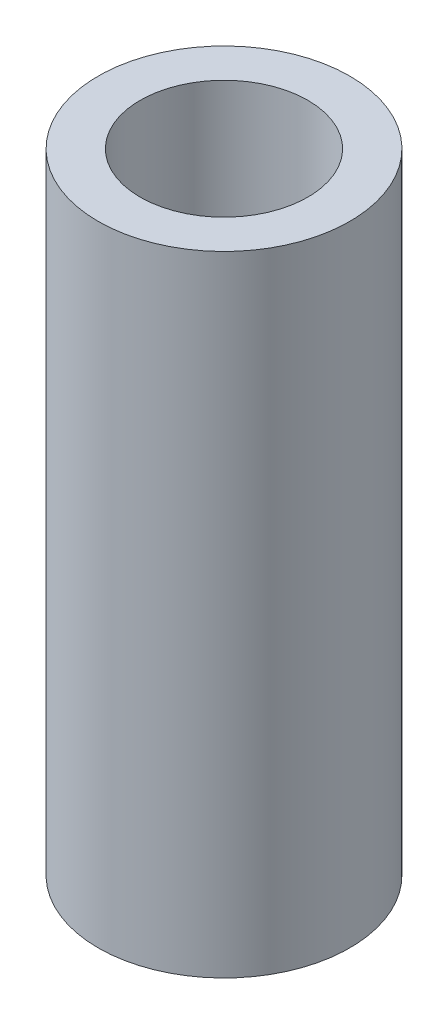
SolidWorks part; units mm, degrees
ref_plane "Front Plane" through (0, 0, 0) normal (0, 0, 1) x (1, 0, 0)
ref_plane "Top Plane" through (0, 0, 0) normal (0, 1, 0) x (1, 0, 0)
ref_plane "Right Plane" through (0, 0, 0) normal (1, 0, 0) x (0, 0, -1)
sketch "Sketch1" plane through (0, 0, 0) normal (0, 1, 0) x (1, 0, 0)
  circle A0 centre (0, 0) radius 6
extrude "Boss-Extrude2" add sketch "Sketch1" along normal blind 30 contours A0
sketch "Sketch2" plane through (0, 30, 0) normal (0, 1, 0) x (1, 0, 0)
  circle A0 centre (0, 0) radius 4
extrude "Cut-Extrude1" cut sketch "Sketch2" against normal blind 10
sketch "Sketch3" plane through (0, 0, 0) normal (0, -1, 0) x (-1, 0, 0)
  circle A0 centre (0, 0) radius 3
extrude "Cut-Extrude2" cut sketch "Sketch3" against normal blind 10
